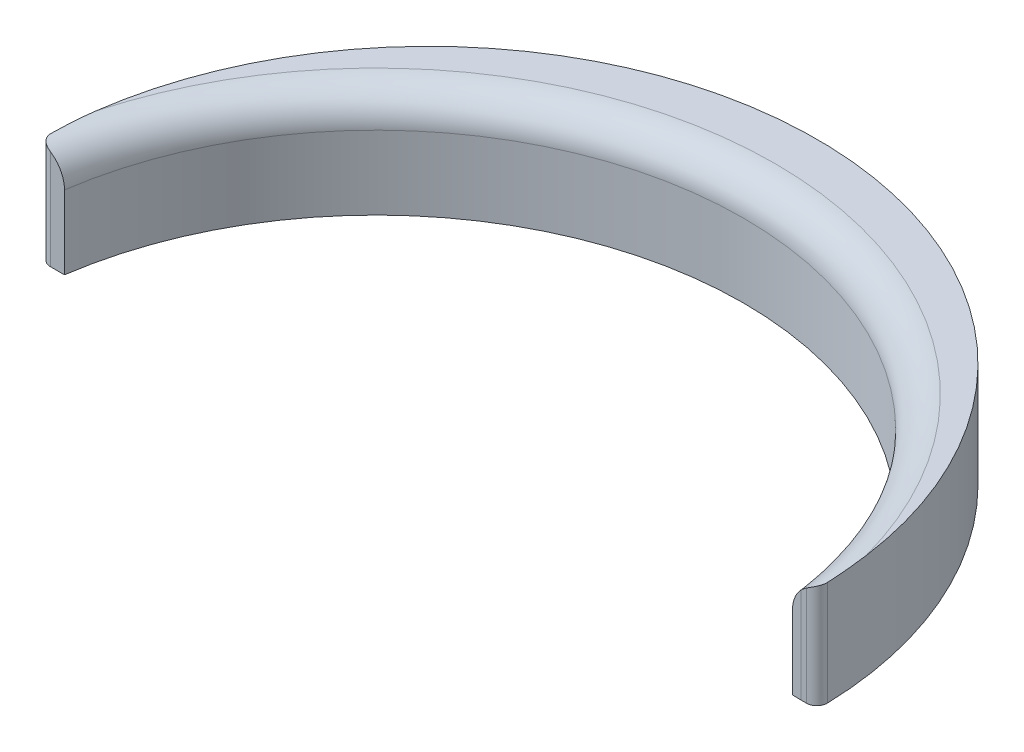
SolidWorks part; units mm, degrees
ref_plane "前视基准面" through (0, 0, 0) normal (0, 0, 1) x (1, 0, 0)
ref_plane "上视基准面" through (0, 0, 0) normal (0, 1, 0) x (1, 0, 0)
ref_plane "右视基准面" through (0, 0, 0) normal (1, 0, 0) x (0, 0, -1)
sketch "草图1" plane through (0, 0, 0) normal (0, 1, 0) x (1, 0, 0)
  line L0 (35.1777, -0.2532) -> (35.6673, -0.2532)
  line L1 (-35.8152, -0.2532) -> (-36.3049, -0.2532)
  line L2 (-35.8152, -0.2532) -> (-34.9598, -0.2532)
  line L3 (35.1777, -0.2532) -> (34.3188, -0.2296)
  circle A0 centre (-0.3188, -5.2532) radius 32.5 construction
  circle A1 centre (-0.3188, 19.7468) radius 11 construction
  circle A2 centre (-0.3188, 19.7468) radius 10 construction
  arc A3 (35.6673, -0.2532) -> (36.667, 0.7745) centre (35.6673, 0.7468) ccw
  arc A5 (36.667, 0.7745) -> (-37.3045, 0.7745) centre (-0.3188, -0.2532) ccw
  arc A6 (34.3188, -0.2296) -> (-34.9598, -0.2532) centre (-0.3188, -5.2532) ccw
  arc A8 (-36.3049, -0.2532) -> (-37.3045, 0.7745) centre (-36.3049, 0.7468) cw
  point P12 (36.6812, -0.2532)
  point P19 (-37.3188, -0.2532)
  dimension "D1" = 1
  dimension "D2" = 37
  dimension "D3" = 35
  dimension "D4" = 65
  dimension "D5" = 20
  dimension "D6" = 22
extrude "凸台-拉伸1" add sketch "草图1" along normal blind 10
fillet "圆角2" radius 3 1 edges at (-0.3307, 10, -29.7468)
sketch "草图2" plane through (0, 0, 0) normal (0, -1, 0) x (1, 0, 0)
  circle A0 centre (-0.3188, 0.2532) radius 37 construction
  circle A1 centre (-0.3188, 0.2532) radius 33.5 construction
  circle A2 centre (-15.3188, -29.7009) radius 1.5
  circle A3 centre (14.6812, -29.7009) radius 1.5
  dimension "D1" = 67
  dimension "D2" = 30
extrude "切除-拉伸1" cut sketch "草图2" against normal blind 7
